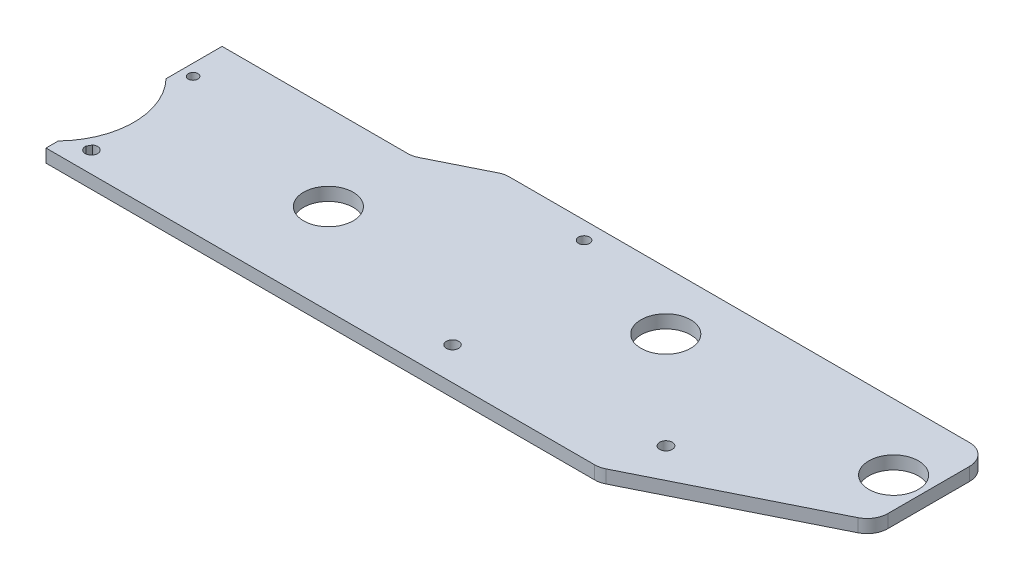
SolidWorks part; units mm, degrees
ref_plane "Front" through (0, 0, 0) normal (0, 0, 1) x (1, 0, 0)
ref_plane "Top" through (0, 0, 0) normal (0, 1, 0) x (1, 0, 0)
ref_plane "Right" through (0, 0, 0) normal (1, 0, 0) x (0, 0, -1)
sketch "Sketch1" plane through (0, 0, 0) normal (0, 1, 0) x (1, 0, 0)
  line L1 (0, 0) -> (210, 0)
  line L2 (0, 0) -> (0, -50)
  line L3 (0, -50) -> (210, -50)
  line L4 (210, 0) -> (210, -50)
  circle A7 centre (3.4895, -16.7877) radius 1.2117
  circle A8 centre (34.3726, -17.194) radius 1.1656
  circle A9 centre (37.5207, -44.9212) radius 1.5
  circle A12 centre (168.9752, -37.4032) radius 1.5173
  circle A13 centre (116, -4.2372) radius 1.3356
  circle A14 centre (12.2576, -3.2748) radius 1.6244
  dimension "D1" = 210
  dimension "D2" = 50
extrude "Boss-Extrude1" add sketch "Sketch1" along normal blind 3.175
sketch "Sketch2" plane through (0, 3.175, 0) normal (0, 1, 0) x (1, 0, 0)
  line L0 (210, 0) -> (0, 0) construction
  line L1 (0, 0) -> (0, -50) construction
  circle A0 centre (10, -26) radius 2
  circle A1 centre (10, -42) radius 2
  circle A2 centre (26, -26) radius 2
  circle A3 centre (26, -42) radius 2
  dimension "D1" = 16
  dimension "D2" = 16
  dimension "D3" = 16
  dimension "D4" = 26
  dimension "D5" = 10
  dimension "D6" = 10
  dimension "D7" = 26
  dimension "D8" = 16
extrude "Cut-Extrude1" cut sketch "Sketch2" against normal blind 10
sketch "Sketch3" plane through (0, 3.175, 0) normal (0, 1, 0) x (1, 0, 0)
  line L0 (210, 0) -> (0, 0) construction
  line L1 (210, 0) -> (0, 0) construction
  circle A0 centre (78.0103, -28.1) radius 6
  circle A1 centre (145.5313, -14) radius 6
  circle A2 centre (18, -34) radius 0.587
  circle A3 centre (26, -26) radius 2 construction
  circle A4 centre (202.6463, -16) radius 6
  dimension "D1" = 28.1
  dimension "D3" = 16
  dimension "D4" = 14
  dimension "D7" = 125.222
  dimension "D2" = 60.2996
  dimension "D5" = 8
  dimension "D6" = 8
  dimension "D8" = 57.15
extrude "Cut-Extrude2" cut sketch "Sketch3" against normal blind 57.15
sketch "Sketch4" [suppressed] plane through (0, 3.175, 0) normal (0, 1, 0) x (1, 0, 0)
  line L0 (3.4895, -16.7877) -> (18, -34)
  line L1 (3.4895, -20.6627) -> (5.9498, -23.5811)
  line L2 (18, -34) -> (34.3726, -17.194)
  line L3 (34.3726, -17.194) -> (75.8499, -28.1)
  line L4 (75.8499, -28.1) -> (37.5207, -44.9212)
  line L5 (7.3432, -17.194) -> (9.8664, -20.303)
  circle A0 centre (18, -34) radius 15.9299
  circle A1 centre (3.4895, -16.7877) radius 3.8751
  circle A2 centre (34.3726, -17.194) radius 3.7227
  circle A3 centre (37.5207, -44.9212) radius 3.8676
  circle A4 centre (75.8499, -28.1) radius 12.797
  circle A5 centre (112.3021, -4.7393) radius 5.1588
  circle A6 centre (118.879, -40.0177) radius 4.9035
  circle A7 centre (140.772, -16) radius 12.6375
  circle A8 centre (168.9752, -37.4032) radius 4.2066
  circle A9 centre (197.922, -16) radius 12.8
sketch "Sketch5" [suppressed] plane through (0, 3.175, 0) normal (0, 1, 0) x (1, 0, 0)
  line L0 (210, 0) -> (0, 0) construction
  line L2 (-0.6266, -16.7877) -> (37.5207, -16.7877)
  line L3 (-0.6266, -16.7877) -> (-0.6266, -44.9212)
  line L4 (-0.6266, -44.9212) -> (37.5207, -44.9212)
  line L5 (37.5207, -16.7877) -> (37.5207, -44.9212)
  line L6 (75.8499, -15.182) -> (37.5207, -15.182)
  line L7 (75.8499, -15.182) -> (75.8499, -44.9212)
  line L8 (75.8499, -44.9212) -> (37.5207, -44.9212)
  line L9 (37.5207, -15.182) -> (37.5207, -44.9212)
  line L10 (112.3021, -4.7393) -> (75.8499, -4.7393)
  line L11 (112.3021, -4.7393) -> (112.3021, -44.9212)
  line L12 (112.3021, -44.9212) -> (75.8499, -44.9212)
  line L13 (75.8499, -4.7393) -> (75.8499, -44.9212)
  line L14 (112.3021, -4.7393) -> (102.3945, -4.7393)
  line L16 (112.3021, -4.7393) -> (112.3021, 0)
  line L17 (112.3021, 0) -> (102.3945, 0)
  line L18 (102.3945, -4.7393) -> (102.3945, 0)
  line L19 (210, -50) -> (210, 0) construction
  line L20 (112.3021, -4.7393) -> (123.1553, -4.7393)
  line L21 (112.3021, -4.7393) -> (112.3021, 0)
  line L22 (112.3021, 0) -> (123.1553, 0)
  line L23 (123.1553, -4.7393) -> (123.1553, 0)
  line L24 (112.3021, -4.7393) -> (140.772, -4.7393)
  line L25 (112.3021, -4.7393) -> (112.3021, -40.0177)
  line L26 (112.3021, -40.0177) -> (140.772, -40.0177)
  line L27 (140.772, -4.7393) -> (140.772, -40.0177)
  line L28 (140.772, -16) -> (168.9752, -16)
  line L29 (140.772, -16) -> (140.772, -40.0177)
  line L30 (140.772, -40.0177) -> (168.9752, -40.0177)
  line L31 (168.9752, -16) -> (168.9752, -40.0177)
  line L32 (168.9752, -4.7393) -> (210, -4.7393)
  line L33 (168.9752, -4.7393) -> (168.9752, -40.0177)
  line L34 (168.9752, -40.0177) -> (210, -40.0177)
  line L35 (210, -4.7393) -> (210, -40.0177)
  line L36 (0, -50) -> (210, -50) construction
  line L37 (160.7629, -40.0177) -> (177.2091, -40.0177)
  line L38 (160.7629, -40.0177) -> (160.7629, -44.9212)
  line L39 (160.7629, -44.9212) -> (177.2091, -44.9212)
  line L40 (177.2091, -40.0177) -> (177.2091, -44.9212)
  line L41 (112.3021, -40.0177) -> (126.3591, -40.0177)
  line L42 (112.3021, -40.0177) -> (112.3021, -47.7828)
  line L43 (112.3021, -47.7828) -> (126.3591, -47.7828)
  line L44 (126.3591, -40.0177) -> (126.3591, -47.7828)
  line L45 (30.5963, -44.9212) -> (44.6115, -44.9212)
  line L46 (30.5963, -44.9212) -> (30.5963, -50)
  line L47 (30.5963, -50) -> (44.6115, -50)
  line L48 (44.6115, -44.9212) -> (44.6115, -50)
  line L50 (-0.6266, -44.9212) -> (30.5963, -44.9212)
  line L51 (-0.6266, -44.9212) -> (-0.6266, -50)
  line L52 (-0.6266, -50) -> (30.5963, -50)
  line L53 (30.5963, -44.9212) -> (30.5963, -50)
  circle A0 centre (3.4895, -16.7877) radius 4.1161
  circle A1 centre (34.3726, -17.194) radius 3.8132
  circle A2 centre (75.8499, -28.1) radius 12.918
  circle A3 centre (112.3021, -4.7393) radius 5.2663
  circle A4 centre (140.772, -16) radius 13.0245
  circle A5 centre (197.922, -16) radius 12.3805
  circle A6 centre (168.9752, -37.4032) radius 4.7643
  circle A7 centre (118.879, -40.0177) radius 5.279
  circle A8 centre (37.5207, -44.9212) radius 4.2049
  line M12 (0, 0) -> (0, -50)
  line M13 (0, -50) -> (210, -50)
  line M14 (210, -50) -> (210, 0)
  line M15 (210, 0) -> (0, 0)
extrude "Cut-Extrude5" [suppressed] cut sketch "Sketch5" against normal blind 11.52 contours A5 L32 L23 L24 A4 L28 L33 M14 M15 | A1 L6 L13 L10 L18 A0 L2 M15 M12 | L8 L48 L34 L40 L39 L38 L30 L26 L44 L43 L42 L12 M13 M14
fillet "Fillet1" [suppressed] radius 5
sketch "Sketch10" plane through (0, 3.175, 0) normal (0, 1, 0) x (1, 0, 0)
  line L0 (210, -27.8594) -> (165.5029, -50)
  line L1 (210, -50) -> (210, 0) construction
  line L2 (0, -50) -> (210, -50) construction
  line L3 (165.5029, -50) -> (210, -50)
  line L4 (210, -50) -> (210, -27.8594)
  line L5 (92.5326, 0) -> (77.6548, -7.4028)
  line L6 (210, 0) -> (0, 0) construction
  line L7 (77.6548, -7.4028) -> (0, -7.4028)
  line L8 (0, 0) -> (0, -50) construction
  line L9 (0, -7.4028) -> (0, 0)
  line L10 (0, 0) -> (92.5326, 0)
extrude "Cut-Extrude7" cut sketch "Sketch10" against normal blind 10
fillet "Fillet3" radius 5 7 edges at (0, 1.5875, 50) (0, 1.5875, 7.4028) (77.6548, 1.5875, 7.4028) (92.5326, 1.5875, 0) (210, 1.5875, 0) (210, 1.5875, 27.8594) (165.5029, 1.5875, 50)
sketch "Sketch11" plane through (0, 3.175, 0) normal (0, 1, 0) x (1, 0, 0)
  circle A0 centre (18, -34) radius 18.5
  circle A1 centre (10, -26) radius 2
  circle A2 centre (10, -42) radius 2
  circle A3 centre (26, -26) radius 2
  circle A4 centre (26, -42) radius 2
extrude "Boss-Extrude4" add sketch "Sketch11" against normal blind 3.175
sketch "Sketch12" plane through (0, 3.175, 0) normal (0, 1, 0) x (1, 0, 0)
  circle A0 centre (18, -34) radius 21
  circle A1 centre (10, -26) radius 2 construction
  circle A2 centre (10, -42) radius 2 construction
  dimension "D1" = 8
  dimension "D2" = 8
extrude "Boss-Extrude5" add sketch "Sketch12" against normal blind 3.175
sketch "Sketch13" plane through (0, 3.175, 0) normal (0, 1, 0) x (1, 0, 0)
  circle A0 centre (18, -34) radius 18.85
extrude "Cut-Extrude8" cut sketch "Sketch13" against normal blind 3.175
sketch "Sketch14" plane through (0, 3.175, 0) normal (0, 1, 0) x (1, 0, 0)
  line L0 (0, -12.4028) -> (0, -23.1833) construction
  line L1 (0, -34.2728) -> (-35.83, -34.2728)
  line L2 (0, -34.2728) -> (0, 0.7272)
  line L3 (0, 0.7272) -> (-35.83, 0.7272)
  line L4 (-35.83, -34.2728) -> (-35.83, 0.7272)
  line L5 (5, -7.4028) -> (76.4796, -7.4028) construction
  line L8 (0, 0.7272) -> (18, 0.7272)
  line L9 (0, 0.7272) -> (0, -12.2485)
  line L10 (0, -12.2485) -> (18, -12.2485)
  line L11 (18, 0.7272) -> (18, -12.2485)
  line M20 (76.4796, -7.4028) -> (5, -7.4028)
  arc M21 (5, -7.4028) -> (0, -12.4028) centre (5, -12.4028) ccw
  line M22 (0, -12.4028) -> (0, -23.1833)
  arc M23 (0, -23.1833) -> (0, -44.8167) centre (18, -34) ccw
  dimension "D4" = 18
  dimension "D1" = 8.13
  dimension "D2" = 35.83
  dimension "D3" = 35
extrude "Boss-Extrude6" add sketch "Sketch14" against normal blind 3.175 contours L4 L1 L2 L3 M23 M22 | L11 L8 L2 L10 M21 M20
fillet "Fillet4" radius 5 3 edges at (18, 1.5875, -0.7272) (-35.83, 1.5875, 34.2728) (-35.83, 1.5875, -0.7272)
sketch "Sketch15" plane through (0, 3.175, 0) normal (0, 1, 0) x (1, 0, 0)
  line L0 (210, -24.7625) -> (210, -5) construction
  circle A0 centre (122, -42.0581) radius 1.5
  dimension "D1" = 88
extrude "Cut-Extrude9" cut sketch "Sketch15" against normal blind 10
sketch "Sketch16" plane through (0, 3.175, 0) normal (0, 1, 0) x (1, 0, 0)
  line L0 (18, -4.2728) -> (18, -7.4028) construction
  line L1 (13, 0.7272) -> (-30.83, 0.7272) construction
  circle A0 centre (12, -3.2728) radius 1.5
  dimension "D1" = 6
  dimension "D2" = 4
extrude "Cut-Extrude10" cut sketch "Sketch16" against normal blind 10
sketch "Sketch17" plane through (0, 3.175, 0) normal (0, 1, 0) x (1, 0, 0)
  line L0 (13, 0.7272) -> (-30.83, 0.7272) construction
  line L1 (-35.83, -29.2728) -> (-35.83, -4.2728) construction
  circle A0 centre (-30.83, -15.7728) radius 1.5
  dimension "D1" = 16.5
  dimension "D2" = 5
extrude "Cut-Extrude11" cut sketch "Sketch17" against normal blind 10
sketch "Sketch18" plane through (0, 3.175, 0) normal (0, 1, 0) x (1, 0, 0)
  line L0 (31.6015, -50) -> (31.6015, 19.9413)
  line L1 (31.6015, 19.9413) -> (-46.2316, 19.9413)
  line L2 (-46.2316, 19.9413) -> (-46.2316, -56.2496)
  line L3 (-46.2316, -56.2496) -> (31.6015, -57.6922)
  line L4 (31.6015, -57.6922) -> (31.6015, -50)
extrude "Cut-Extrude12" cut sketch "Sketch18" against normal blind 10
